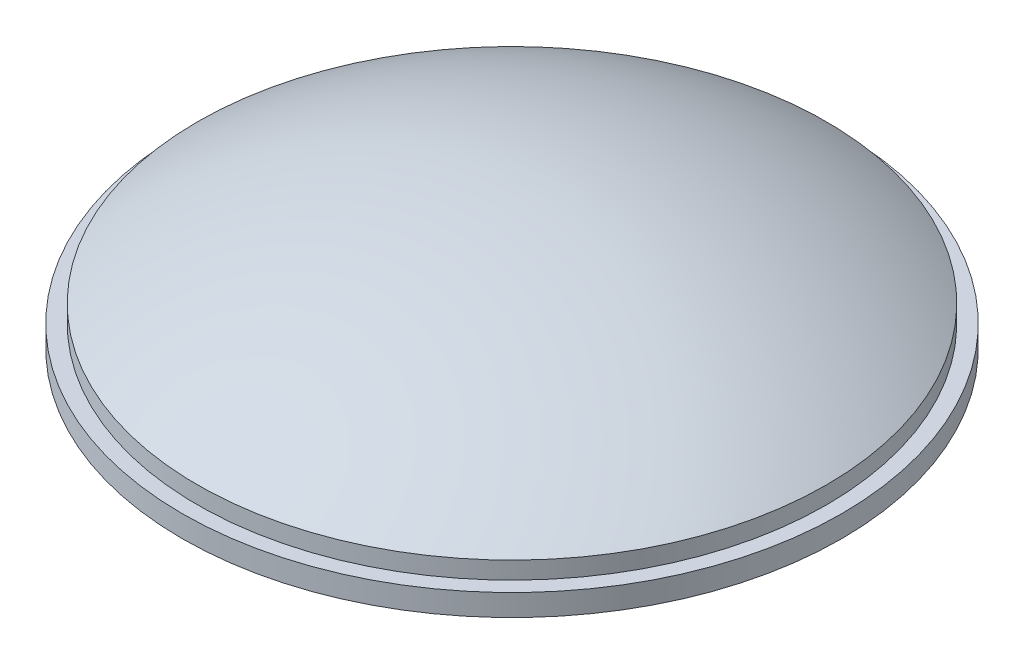
SolidWorks part; units mm, degrees
ref_plane "Front" through (0, 0, 0) normal (0, 0, 1) x (1, 0, 0)
ref_plane "Top" through (0, 0, 0) normal (0, 1, 0) x (1, 0, 0)
ref_plane "Right" through (0, 0, 0) normal (1, 0, 0) x (0, 0, -1)
sketch "Sketch1" plane through (0, 0, 0) normal (0, 0, 1) x (1, 0, 0)
  line L0 (72.5, 40) -> (72.5, 36)
  line L1 (72.5, 36) -> (76, 36)
  line L2 (76, 36) -> (76, 31)
  line L3 (76, 31) -> (73, 31)
  line L4 (73, 31) -> (67, 25)
  line L5 (67, 25) -> (51, 25)
  line L6 (51, 25) -> (26, 0)
  line L7 (26, 0) -> (0, 0)
  line L8 (0, 0) -> (0, 62.2)
  line L9 (0, 0) -> (0, -50) construction
  arc A0 (0, 62.2) -> (72.5, 40) centre (0, -67.284) cw
  point P3 (0, 0)
  point P14 (0, -8.3902)
  point P15 (0, 0)
  dimension "D1" = 5
  dimension "D2" = 3.5
  dimension "D3" = 3
  dimension "D4" = 45
  dimension "D5" = 76
  dimension "D6" = 6
  dimension "D7" = 25
  dimension "D8" = 16
  dimension "D9" = 50
  dimension "D10" = 4
  dimension "D11" = 62.2
revolve "Revolve1" add sketch "Sketch1" angle 360 about L9
sketch "Sketch2" plane through (0, 0, 0) normal (0, -1, 0) x (1, 0, 0)
  line L0 (0, 0) -> (65, 0) construction
  line L1 (30, -90) -> (100, -90)
  line L2 (30, -90) -> (30, 90)
  line L3 (30, 90) -> (100, 90)
  line L4 (100, -90) -> (100, 90)
  line L5 (30, -90) -> (100, 90) construction
  line L6 (30, 90) -> (100, -90) construction
  point P0 (65, 0)
  dimension "D1" = 30
  dimension "D2" = 180
  dimension "D3" = 70
extrude "Cut-Extrude1" cut sketch "Sketch2" against normal up to surface (25 mm away) up to face at (-67, 25, 0)
